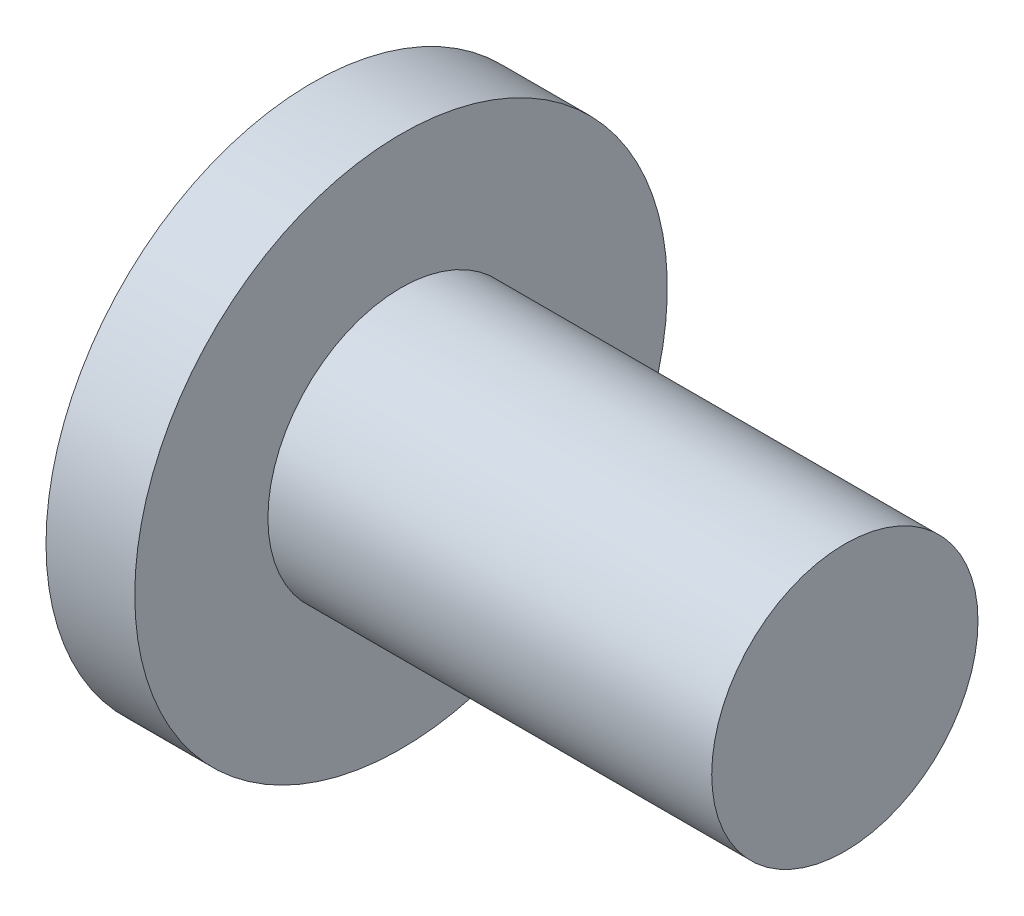
SolidWorks part; units mm, degrees
ref_plane "Front Plane" through (0, 0, 0) normal (0, 0, 1) x (1, 0, 0)
ref_plane "Top Plane" through (0, 0, 0) normal (0, 1, 0) x (1, 0, 0)
ref_plane "Right Plane" through (0, 0, 0) normal (1, 0, 0) x (0, 0, -1)
sketch "Sketch1" plane through (0, 0, 0) normal (0, 0, 1) x (1, 0, 0)
  line L0 (0, 0) -> (8187.4135, 0) construction
  line L1 (0, 0) -> (-12, 0)
  line L2 (-12, 0) -> (-12, 6)
  line L3 (-12, 6) -> (-10, 6)
  line L4 (-10, 6) -> (-10, 3)
  line L5 (-10, 3) -> (0, 3)
  line L6 (0, 3) -> (0, 0)
  dimension "D1" = 3
  dimension "D2" = 6
  dimension "D3" = 2
  dimension "D4" = 10
revolve "Revolve1" add sketch "Sketch1" angle 360 about L0
